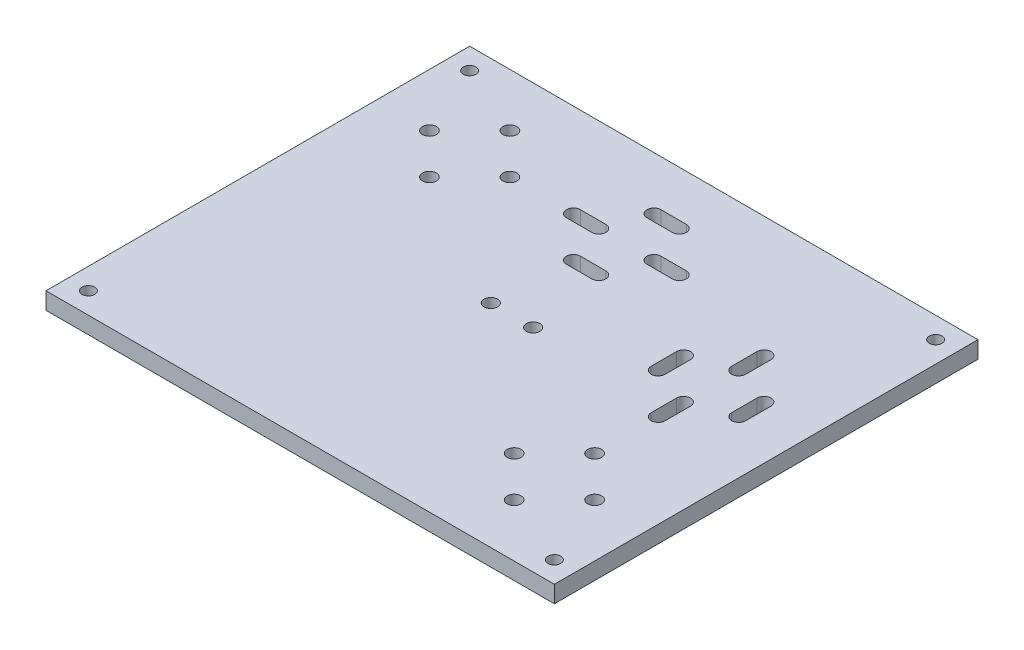
SolidWorks part; units mm, degrees
ref_plane "Front Plane" through (0, 0, 0) normal (0, 0, 1) x (1, 0, 0)
ref_plane "Top Plane" through (0, 0, 0) normal (0, 1, 0) x (1, 0, 0)
ref_plane "Right Plane" through (0, 0, 0) normal (1, 0, 0) x (0, 0, -1)
sketch "Sketch2" plane through (0, 0, 0) normal (0, 1, 0) x (1, 0, 0)
  line L1 (-60, 50) -> (60, 50)
  line L2 (-60, 50) -> (-60, -50)
  line L3 (-60, -50) -> (60, -50)
  line L4 (60, 50) -> (60, -50)
  line L5 (-60, 50) -> (60, -50) construction
  line L6 (-60, -50) -> (60, 50) construction
  point P0 (0, 0)
  dimension "D1" = 100
  dimension "D2" = 120
extrude "Boss-Extrude1" add sketch "Sketch2" along normal blind 4
sketch "Sketch3" plane through (0, 4, 0) normal (0, 1, 0) x (1, 0, 0)
  line L0 (60, -50) -> (60, 50) construction
  line L1 (-55, 45) -> (55, 45) construction
  line L2 (-55, 45) -> (-55, -45) construction
  line L3 (-55, -45) -> (55, -45) construction
  line L4 (55, 45) -> (55, -45) construction
  line L5 (-55, 45) -> (55, -45) construction
  line L6 (-55, -45) -> (55, 45) construction
  line L7 (-60, -50) -> (60, -50) construction
  circle A0 centre (-55, 45) radius 1.5
  circle A1 centre (55, 45) radius 1.5
  circle A2 centre (55, -45) radius 1.5
  circle A3 centre (-55, -45) radius 1.5
  point P0 (0, 0)
  dimension "D3" = 3
  dimension "D1" = 5
  dimension "D2" = 5
extrude "Cut-Extrude1" cut sketch "Sketch3" against normal blind 5
sketch "Sketch4" plane through (0, 4, 0) normal (0, 1, 0) x (1, 0, 0)
  line L0 (60, -50) -> (60, 50) construction
  line L1 (-60, -50) -> (60, -50) construction
  line L2 (60, 50) -> (-60, 50) construction
  line L4 (-60, 50) -> (-60, -50) construction
  circle A0 centre (-38, 28) radius 9.5 construction
  circle A1 centre (-4, 28) radius 9.5 construction
  circle A2 centre (38, 6) radius 9.5 construction
  circle A3 centre (38, -28) radius 9.5 construction
  circle A4 centre (-38, 28) radius 17 construction
  circle A5 centre (38, -28) radius 17 construction
  circle A6 centre (-38, 37.5) radius 1.65
  circle A7 centre (-4, 37.5) radius 1.65
  circle A8 centre (38, 15.5) radius 1.65
  circle A9 centre (38, -18.5) radius 1.65
  circle A10 centre (-28.5, 28) radius 1.65
  circle A11 centre (-38, 18.5) radius 1.65
  circle A12 centre (-47.5, 28) radius 1.65
  circle A13 centre (5.5, 28) radius 1.65
  circle A14 centre (-4, 18.5) radius 1.65
  circle A15 centre (-13.5, 28) radius 1.65
  circle A16 centre (47.5, 6) radius 1.65
  circle A17 centre (38, -3.5) radius 1.65
  circle A18 centre (28.5, 6) radius 1.65
  circle A19 centre (47.5, -28) radius 1.65
  circle A20 centre (38, -37.5) radius 1.65
  circle A21 centre (28.5, -28) radius 1.65
  point P26 (47.5, 6)
  point P27 (47.5, -28)
  dimension "D1" = 19
  dimension "D4" = 34
  dimension "D6" = 22
  dimension "D9" = 3.3
  dimension "D2" = 34
  dimension "D3" = 34
  dimension "D5" = 22
  dimension "D7" = 22
  dimension "D8" = 22
  dimension "D10" = 4
  dimension "D11" = 4
  dimension "D12" = 4
  dimension "D13" = 4
extrude "Cut-Extrude2" cut sketch "Sketch4" against normal blind 5
sketch "Sketch6" plane through (0, 4, 0) normal (0, 1, 0) x (1, 0, 0)
  line L0 (-5, 0) -> (5, 0) construction
  circle A0 centre (5, 0) radius 1.6
  circle A1 centre (-5, 0) radius 1.6
  point P4 (0, 0)
  dimension "D2" = 3.2
  dimension "D1" = 10
extrude "Cut-Extrude3" cut sketch "Sketch6" against normal blind 5
sketch "Sketch7" plane through (0, 4, 0) normal (0, 1, 0) x (1, 0, 0)
  line L0 (-4, 37.5) -> (2, 37.5) construction
  line L1 (-4, 39.15) -> (2, 39.15)
  line L2 (-4, 35.85) -> (2, 35.85)
  line L3 (5.5, 28) -> (11.5, 28) construction
  line L4 (5.5, 29.65) -> (11.5, 29.65)
  line L5 (5.5, 26.35) -> (11.5, 26.35)
  line L6 (-4, 18.5) -> (2, 18.5) construction
  line L7 (-4, 20.15) -> (2, 20.15)
  line L8 (-4, 16.85) -> (2, 16.85)
  line L9 (-13.5, 28) -> (-7.5, 28) construction
  line L10 (-13.5, 29.65) -> (-7.5, 29.65)
  line L11 (-13.5, 26.35) -> (-7.5, 26.35)
  line L12 (38, 15.5) -> (38, 21.5) construction
  line L13 (36.35, 15.5) -> (36.35, 21.5)
  line L14 (39.65, 15.5) -> (39.65, 21.5)
  line L15 (47.5, 6) -> (47.5, 12) construction
  line L16 (45.85, 6) -> (45.85, 12)
  line L17 (49.15, 6) -> (49.15, 12)
  line L18 (38, -3.5) -> (38, 2.5) construction
  line L19 (36.35, -3.5) -> (36.35, 2.5)
  line L20 (39.65, -3.5) -> (39.65, 2.5)
  line L21 (28.5, 6) -> (28.5, 12) construction
  line L22 (26.85, 6) -> (26.85, 12)
  line L23 (30.15, 6) -> (30.15, 12)
  arc A0 (-4, 39.15) -> (-4, 35.85) centre (-4, 37.5) ccw
  arc A1 (2, 35.85) -> (2, 39.15) centre (2, 37.5) ccw
  arc A2 (5.5, 29.65) -> (5.5, 26.35) centre (5.5, 28) ccw
  arc A3 (11.5, 26.35) -> (11.5, 29.65) centre (11.5, 28) ccw
  arc A4 (-4, 20.15) -> (-4, 16.85) centre (-4, 18.5) ccw
  arc A5 (2, 16.85) -> (2, 20.15) centre (2, 18.5) ccw
  arc A6 (-13.5, 29.65) -> (-13.5, 26.35) centre (-13.5, 28) ccw
  arc A7 (-7.5, 26.35) -> (-7.5, 29.65) centre (-7.5, 28) ccw
  arc A8 (36.35, 15.5) -> (39.65, 15.5) centre (38, 15.5) ccw
  arc A9 (39.65, 21.5) -> (36.35, 21.5) centre (38, 21.5) ccw
  arc A10 (45.85, 6) -> (49.15, 6) centre (47.5, 6) ccw
  arc A11 (49.15, 12) -> (45.85, 12) centre (47.5, 12) ccw
  arc A12 (36.35, -3.5) -> (39.65, -3.5) centre (38, -3.5) ccw
  arc A13 (39.65, 2.5) -> (36.35, 2.5) centre (38, 2.5) ccw
  arc A14 (26.85, 6) -> (30.15, 6) centre (28.5, 6) ccw
  arc A15 (30.15, 12) -> (26.85, 12) centre (28.5, 12) ccw
  circle A16 centre (38, 15.5) radius 1.65 construction
  point P3 (-1, 37.5)
  point P8 (8.5, 28)
  point P16 (-1, 18.5)
  point P24 (-10.5, 28)
  point P32 (38, 18.5)
  point P40 (47.5, 9)
  point P48 (38, -0.5)
  point P56 (28.5, 9)
  dimension "D1" = 6
extrude "Cut-Extrude4" cut sketch "Sketch7" against normal blind 21
